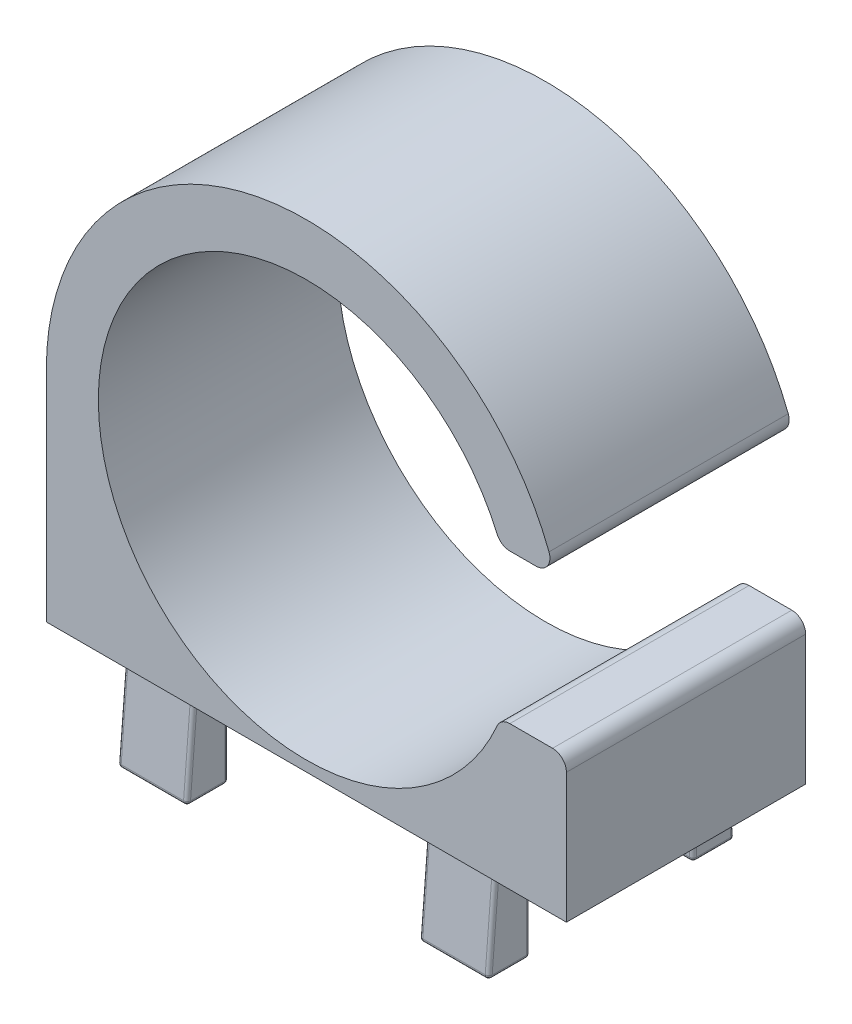
SolidWorks part; units mm, degrees
ref_plane "Front Plane" through (0, 0, 0) normal (0, 0, 1) x (1, 0, 0)
ref_plane "Top Plane" through (0, 0, 0) normal (0, 1, 0) x (1, 0, 0)
ref_plane "Right Plane" through (0, 0, 0) normal (1, 0, 0) x (0, 0, -1)
sketch "Sketch1" plane through (0, 0, 0) normal (0, 0, 1) x (1, 0, 0)
  line L0 (-19.05, 0) -> (-19.05, -16.002)
  line L1 (-19.05, -16.002) -> (19.05, -16.002)
  line L2 (19.05, -16.002) -> (19.05, 0)
  circle A0 centre (0, 0) radius 15.24
  arc A1 (19.05, 0) -> (-19.05, 0) centre (0, 0) ccw
  point P3 (0, -15.24)
  dimension "D1" = 30.48
  dimension "D2" = 3.81
  dimension "D3" = 0.762
extrude "Boss-Extrude1" add sketch "Sketch1" along normal blind 17.526
sketch "Sketch2" plane through (0, 0, 0) normal (1, 0, 0) x (0, 0, -1)
  line L0 (-2.7878, 12.7008) -> (-0.8828, 12.7008)
  line L1 (-0.8828, 12.7008) -> (-0.8828, 5.08)
  line L2 (-0.8828, 5.08) -> (-11.5707, 5.08)
  line L3 (-2.7878, 12.7008) -> (-2.7878, 12.065)
  line L4 (-2.7878, 12.065) -> (-9.7728, 12.065)
  line L5 (-9.7728, 12.065) -> (-9.7728, 13.335)
  line L6 (-9.7728, 13.335) -> (-11.5707, 12.5348)
  line L7 (0, 0) -> (-50000, 0) construction
  line L8 (-11.5707, 5.08) -> (-11.5707, 12.5348)
  point P11 (0, 0)
  dimension "D1" = 25.4015
  dimension "D2" = 26.67
  dimension "D3" = 1.905
  dimension "D4" = 6.985
  dimension "D5" = 24.13
  dimension "D6" = 5.08
revolve "Cut-Revolve1" [suppressed] cut sketch "Sketch2" angle 360 about L7
sketch "Sketch5" plane through (0, 0, 17.526) normal (0, 0, 1) x (1, 0, 0)
  line L0 (19.05, -16.002) -> (19.05, 0) construction
  line L1 (19.05, -5.4742) -> (19.05, 0)
  line L2 (14.2229, 5.4742) -> (18.2465, 5.4742)
  line L3 (14.2229, -5.4742) -> (19.05, -5.4742)
  arc A0 (19.05, 0) -> (-19.05, 0) centre (0, 0) ccw construction
  circle A1 centre (0, 0) radius 15.24 construction
  arc A2 (19.05, 0) -> (18.2465, 5.4742) centre (0, 0) ccw
  arc A3 (14.2229, -5.4742) -> (14.2229, 5.4742) centre (0, 0) ccw
  dimension "D1" = 5.4742
  dimension "D2" = 5.4742
extrude "Cut-Extrude2" cut sketch "Sketch5" against normal through all
sketch "Sketch3" plane through (19.05, 0, 0) normal (1, 0, 0) x (0, 0, -1)
  line L0 (-2.794, -16.002) -> (-2.794, -22.352)
  line L1 (-17.526, -16.002) -> (0, -16.002) construction
  line L2 (-2.794, -22.352) -> (0.254, -22.352)
  line L3 (0.254, -22.352) -> (-0.254, -16.002)
  line L4 (-0.254, -16.002) -> (-2.794, -16.002)
  line L5 (-14.732, -16.002) -> (-14.732, -22.352)
  line L6 (-14.732, -22.352) -> (-17.78, -22.352)
  line L7 (-17.78, -22.352) -> (-17.272, -16.002)
  line L8 (-17.272, -16.002) -> (-14.732, -16.002)
  line L9 (-14.732, -16.002) -> (-2.794, -16.002) construction
  point P8 (3.4126, -13.97)
  point P11 (-8.763, -16.002)
  dimension "D1" = 17.018
  dimension "D2" = 0.508
  dimension "D3" = 2.54
  dimension "D4" = 6.35
extrude "Boss-Extrude2" add sketch "Sketch3" against normal up to surface (38.1 mm away) up to face at (-19.05, -8.001, 8.763)
sketch "Sketch4" plane through (0, 0, 0) normal (0, 0, -1) x (-1, 0, 0)
  line L0 (19.05, -16.002) -> (-19.05, -16.002) construction
  line L1 (-8.509, -16.002) -> (8.509, -16.002)
  line L2 (-8.509, -16.002) -> (-8.509, -22.352)
  line L3 (-8.509, -22.352) -> (8.509, -22.352)
  line L4 (8.509, -16.002) -> (8.509, -22.352)
  line L5 (19.05, -22.352) -> (-19.05, -22.352) construction
  line L7 (19.05, -16.002) -> (-19.05, -16.002) construction
  line L8 (13.589, -22.352) -> (19.05, -22.352)
  line L9 (13.589, -22.352) -> (13.589, -16.002)
  line L10 (13.589, -16.002) -> (19.05, -16.002)
  line L11 (19.05, -22.352) -> (19.05, -16.002)
  line L13 (-13.589, -22.352) -> (-19.05, -22.352)
  line L14 (-13.589, -22.352) -> (-13.589, -16.002)
  line L15 (-13.589, -16.002) -> (-19.05, -16.002)
  line L16 (-19.05, -22.352) -> (-19.05, -16.002)
  point P9 (0, -16.002)
  dimension "D2" = 17.018
  dimension "D3" = 5.08
  dimension "D1" = 5.08
extrude "Cut-Extrude1" cut sketch "Sketch4" against normal through all and the other way through all
fillet "Fillet1" radius 0.254 32 edges at (11.049, -22.352, 14.732) (8.509, -22.352, 16.256) (11.049, -22.352, 17.78) (13.589, -22.352, 16.256) (-11.049, -22.352, 17.78) (-8.509, -22.352, 16.256) (-11.049, -22.352, 14.732) (-13.589, -22.352, 16.256) (11.049, -22.352, -0.254) (8.509, -22.352, 1.27) (11.049, -22.352, 2.794) (13.589, -22.352, 1.27) (-11.049, -22.352, 2.794) (-8.509, -22.352, 1.27) (-11.049, -22.352, -0.254) (-13.589, -22.352, 1.27) (-8.509, -19.177, 17.526) (-13.589, -19.177, 17.526) (-13.589, -19.177, 14.732) (-8.509, -19.177, 14.732) (-13.589, -19.177, 0) (-13.589, -19.177, 2.794) (-8.509, -19.177, 0) (-8.509, -19.177, 2.794) (13.589, -19.177, 2.794) (13.589, -19.177, 0) (8.509, -19.177, 0) (8.509, -19.177, 2.794) (8.509, -19.177, 17.526) (8.509, -19.177, 14.732) (13.589, -19.177, 17.526) (13.589, -19.177, 14.732)
fillet "Fillet2" radius 1.016 4 edges at (19.05, -5.4742, 8.763) (14.2229, -5.4742, 8.763) (14.2229, 5.4742, 8.763) (18.2465, 5.4742, 8.763)
equation "\"D1@Sketch4\"=\"D3@Sketch4\""
equation "\"D2@Sketch5\"=\"D1@Sketch5\""
